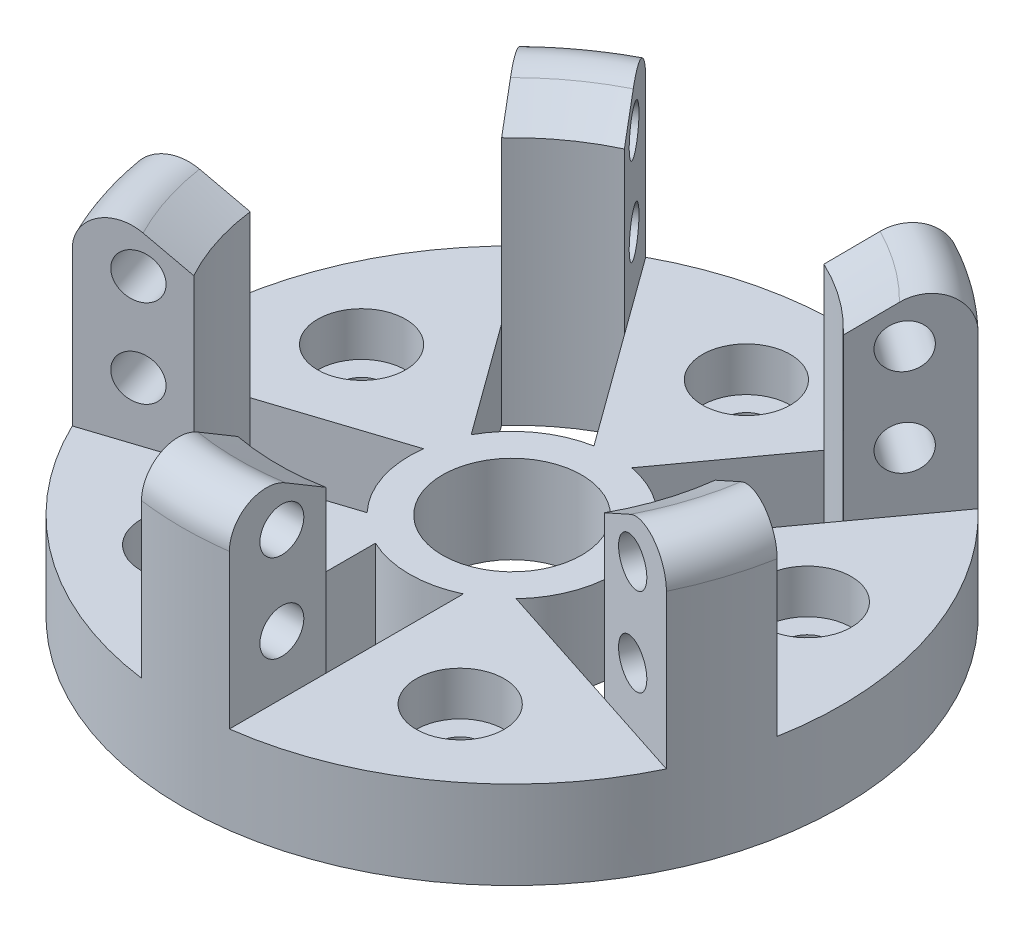
SolidWorks part; units mm, degrees
ref_plane "前视基准面" through (0, 0, 0) normal (0, 0, 1) x (1, 0, 0)
ref_plane "上视基准面" through (0, 0, 0) normal (0, 1, 0) x (1, 0, 0)
ref_plane "右视基准面" through (0, 0, 0) normal (1, 0, 0) x (0, 0, -1)
other "Configuration Table"
sketch "草图2" plane through (0, 0, 0) normal (1, 0, 0) x (0, 0, -1)
  line L0 (0, 43.5346) -> (0, -36.4026) construction
  line L1 (-63.5932, 0) -> (69.8336, 0) construction
  line L2 (0, 0) -> (-45, 0)
  line L3 (-45, 0) -> (-45, 33)
  line L4 (-37.4096, 37.2766) -> (-32, 34)
  line L5 (-32, 34) -> (-32, 12)
  line L6 (-32, 12) -> (0, 12)
  line L7 (0, 12) -> (0, 0)
  arc A0 (-37.4096, 37.2766) -> (-45, 33) centre (-40, 33) ccw
  dimension "D1" = 5
  dimension "D2" = 90
  dimension "D3" = 32
  dimension "D4" = 12
  dimension "D5" = 22
  dimension "D6" = 21
revolve "旋转1" add sketch "草图2" angle 360 about L0
sketch "草图3" plane through (0, 12, 0) normal (0, 1, 0) x (1, 0, 0)
  line L0 (0, 0) -> (0, -45) construction
  line L1 (0, 0) -> (-42.7975, -13.9058) construction
  line L2 (0, 0) -> (-26.4503, 36.4058) construction
  line L3 (0, 0) -> (26.4503, 36.4058) construction
  line L4 (0, 0) -> (42.7975, -13.9058) construction
  line L6 (6, -12.6491) -> (6, -44.5982)
  line L7 (-6, -12.6491) -> (-6, -44.5982)
  line L8 (-13.8841, 1.7975) -> (-44.2695, -8.0753)
  line L9 (-10.1759, -9.6151) -> (-40.5613, -19.4879)
  line L10 (-2.5809, 13.7601) -> (-21.3601, 39.6074)
  line L11 (-12.2891, 6.7066) -> (-31.0683, 32.554)
  line L12 (12.2891, 6.7066) -> (31.0683, 32.554)
  line L13 (2.5809, 13.7601) -> (21.3601, 39.6074)
  line L14 (10.1759, -9.6151) -> (40.5613, -19.4879)
  line L15 (13.8841, 1.7975) -> (44.2695, -8.0753)
  circle A0 centre (0, 0) radius 45 construction
  arc A1 (-40.5613, -19.4879) -> (-6, -44.5982) centre (0, 0) ccw
  arc A2 (-12.2891, 6.7066) -> (-13.8841, 1.7975) centre (0, 0) ccw
  arc A3 (6, -44.5982) -> (40.5613, -19.4879) centre (0, 0) ccw
  arc A4 (44.2695, -8.0753) -> (31.0683, 32.554) centre (0, 0) ccw
  arc A5 (21.3601, 39.6074) -> (-21.3601, 39.6074) centre (0, 0) ccw
  arc A6 (-31.0683, 32.554) -> (-44.2695, -8.0753) centre (0, 0) ccw
  arc A7 (2.5809, 13.7601) -> (-2.5809, 13.7601) centre (0, 0) ccw
  arc A8 (13.8841, 1.7975) -> (12.2891, 6.7066) centre (0, 0) ccw
  arc A9 (6, -12.6491) -> (10.1759, -9.6151) centre (0, 0) ccw
  arc A10 (-10.1759, -9.6151) -> (-6, -12.6491) centre (0, 0) ccw
  point P10 (0, 0)
  point P36 (0, 0)
  dimension "D1" = 28
  dimension "D2" = 5
  dimension "D3" = 12
  dimension "D4" = 5
extrude "切除-拉伸2" cut sketch "草图3" along normal through all contours L7 A1 L9 A10
sketch "草图6" plane through (0, 12, 0) normal (0, 1, 0) x (1, 0, 0)
  line L0 (-30.4419, 0) -> (28.6056, 0) construction
  line L1 (0, 24.2934) -> (0, -23.1923) construction
  line L2 (-6, -31.4325) -> (-6, -12.6491)
  line L3 (6, -31.4325) -> (6, -12.6491)
  line L4 (-31.7482, -4.0068) -> (-13.8841, 1.7975)
  line L5 (-28.04, -15.4195) -> (-10.1759, -9.6151)
  line L6 (-13.6214, 28.9561) -> (-2.5809, 13.7601)
  line L7 (-23.3296, 21.9027) -> (-12.2891, 6.7066)
  line L8 (23.3296, 21.9027) -> (12.2891, 6.7066)
  line L9 (13.6214, 28.9561) -> (2.5809, 13.7601)
  line L10 (28.04, -15.4195) -> (10.1759, -9.6151)
  line L11 (31.7482, -4.0068) -> (13.8841, 1.7975)
  circle A0 centre (0, 32) radius 3
  circle A1 centre (0, 0) radius 32 construction
  circle A2 centre (0, 0) radius 9.5
  arc A3 (-6, -12.6491) -> (6, -12.6491) centre (0, 0) ccw
  arc A4 (10.1759, -9.6151) -> (13.8841, 1.7975) centre (0, 0) ccw
  arc A5 (12.2891, 6.7066) -> (2.5809, 13.7601) centre (0, 0) ccw
  arc A6 (-2.5809, 13.7601) -> (-12.2891, 6.7066) centre (0, 0) ccw
  arc A7 (-13.8841, 1.7975) -> (-10.1759, -9.6151) centre (0, 0) ccw
  circle A8 centre (30.4338, 9.8885) radius 3
  circle A9 centre (18.8091, -25.8885) radius 3
  circle A10 centre (-18.8091, -25.8885) radius 3
  circle A11 centre (-30.4338, 9.8885) radius 3
  point P34 (0, 0)
  point P42 (0, 0)
  arc M1 (-31.7482, -4.0068) -> (-28.04, -15.4195) centre (0, 0) ccw
  arc M5 (-6, -31.4325) -> (6, -31.4325) centre (0, 0) ccw
  arc M9 (28.04, -15.4195) -> (31.7482, -4.0068) centre (0, 0) ccw
  arc M13 (23.3296, 21.9027) -> (13.6214, 28.9561) centre (0, 0) ccw
  arc M17 (-13.6214, 28.9561) -> (-23.3296, 21.9027) centre (0, 0) ccw
  dimension "D1" = 6
  dimension "D2" = 64
  dimension "D3" = 19
  dimension "D4" = 28
  dimension "D5" = 5
extrude "切除-拉伸3" cut sketch "草图6" against normal through all contours A5 L8 L9 M13 | A4 L10 L11 M9 | A3 L2 L3 M5 | A7 L4 L5 M1 | A6 L6 L7 M17 | A11 | A2 | A0 | A9 | A10 | A8
sketch "草图7" plane through (0, 12, 0) normal (0, 1, 0) x (1, 0, 0)
  line L20 (13.8841, 1.7975) -> (31.7482, -4.0068)
  line L21 (31.7482, -4.0068) -> (44.2695, -8.0753)
  line L22 (31.0683, 32.554) -> (23.3296, 21.9027)
  line L23 (23.3296, 21.9027) -> (12.2891, 6.7066)
  line L24 (2.5809, 13.7601) -> (13.6214, 28.9561)
  line L25 (13.6214, 28.9561) -> (21.3601, 39.6074)
  line L26 (-21.3601, 39.6074) -> (-13.6214, 28.9561)
  line L27 (-13.6214, 28.9561) -> (-2.5809, 13.7601)
  line L28 (-12.2891, 6.7066) -> (-23.3296, 21.9027)
  line L29 (-23.3296, 21.9027) -> (-31.0683, 32.554)
  line L30 (-44.2695, -8.0753) -> (-31.7482, -4.0068)
  line L31 (-31.7482, -4.0068) -> (-13.8841, 1.7975)
  line L32 (-10.1759, -9.6151) -> (-28.04, -15.4195)
  line L33 (-28.04, -15.4195) -> (-40.5613, -19.4879)
  line L34 (-6, -44.5982) -> (-6, -31.4325)
  line L35 (-6, -31.4325) -> (-6, -12.6491)
  line L36 (6, -12.6491) -> (6, -31.4325)
  line L37 (6, -31.4325) -> (6, -44.5982)
  line L38 (40.5613, -19.4879) -> (28.04, -15.4195)
  line L39 (28.04, -15.4195) -> (10.1759, -9.6151)
  line L40 (13.8841, 1.7975) -> (31.7482, -4.0068)
  line L41 (31.7482, -4.0068) -> (44.2695, -8.0753)
  line L42 (31.0683, 32.554) -> (23.3296, 21.9027)
  line L43 (23.3296, 21.9027) -> (12.2891, 6.7066)
  line L44 (2.5809, 13.7601) -> (13.6214, 28.9561)
  line L45 (13.6214, 28.9561) -> (21.3601, 39.6074)
  line L46 (-21.3601, 39.6074) -> (-13.6214, 28.9561)
  line L47 (-13.6214, 28.9561) -> (-2.5809, 13.7601)
  line L48 (-12.2891, 6.7066) -> (-23.3296, 21.9027)
  line L49 (-23.3296, 21.9027) -> (-31.0683, 32.554)
  line L50 (-44.2695, -8.0753) -> (-31.7482, -4.0068)
  line L51 (-31.7482, -4.0068) -> (-13.8841, 1.7975)
  line L52 (-10.1759, -9.6151) -> (-28.04, -15.4195)
  line L53 (-28.04, -15.4195) -> (-40.5613, -19.4879)
  line L54 (-6, -44.5982) -> (-6, -31.4325)
  line L55 (-6, -31.4325) -> (-6, -12.6491)
  line L56 (6, -12.6491) -> (6, -31.4325)
  line L57 (6, -31.4325) -> (6, -44.5982)
  line L58 (40.5613, -19.4879) -> (28.04, -15.4195)
  line L59 (28.04, -15.4195) -> (10.1759, -9.6151)
  circle A0 centre (0, 32) radius 3 construction
  circle A1 centre (30.4338, 9.8885) radius 3 construction
  circle A2 centre (18.8091, -25.8885) radius 3 construction
  circle A3 centre (-18.8091, -25.8885) radius 3 construction
  circle A4 centre (-30.4338, 9.8885) radius 3 construction
  circle A5 centre (0, 32) radius 3
  circle A6 centre (30.4338, 9.8885) radius 3
  circle A7 centre (18.8091, -25.8885) radius 3
  circle A8 centre (-18.8091, -25.8885) radius 3
  circle A9 centre (-30.4338, 9.8885) radius 3
  arc A10 (10.1759, -9.6151) -> (13.8841, 1.7975) centre (0, 0) ccw
  arc A11 (44.2695, -8.0753) -> (31.0683, 32.554) centre (0, 0) ccw
  arc A12 (12.2891, 6.7066) -> (2.5809, 13.7601) centre (0, 0) ccw
  arc A13 (21.3601, 39.6074) -> (-21.3601, 39.6074) centre (0, 0) ccw
  arc A14 (-2.5809, 13.7601) -> (-12.2891, 6.7066) centre (0, 0) ccw
  arc A15 (-31.0683, 32.554) -> (-44.2695, -8.0753) centre (0, 0) ccw
  arc A16 (-13.8841, 1.7975) -> (-10.1759, -9.6151) centre (0, 0) ccw
  arc A17 (-40.5613, -19.4879) -> (-6, -44.5982) centre (0, 0) ccw
  arc A18 (-6, -12.6491) -> (6, -12.6491) centre (0, 0) ccw
  arc A19 (6, -44.5982) -> (40.5613, -19.4879) centre (0, 0) ccw
  arc A20 (10.1759, -9.6151) -> (13.8841, 1.7975) centre (0, 0) ccw
  arc A21 (44.2695, -8.0753) -> (31.0683, 32.554) centre (0, 0) ccw
  arc A22 (12.2891, 6.7066) -> (2.5809, 13.7601) centre (0, 0) ccw
  arc A23 (21.3601, 39.6074) -> (-21.3601, 39.6074) centre (0, 0) ccw
  arc A24 (-2.5809, 13.7601) -> (-12.2891, 6.7066) centre (0, 0) ccw
  arc A25 (-31.0683, 32.554) -> (-44.2695, -8.0753) centre (0, 0) ccw
  arc A26 (-13.8841, 1.7975) -> (-10.1759, -9.6151) centre (0, 0) ccw
  arc A27 (-40.5613, -19.4879) -> (-6, -44.5982) centre (0, 0) ccw
  arc A28 (-6, -12.6491) -> (6, -12.6491) centre (0, 0) ccw
  arc A29 (6, -44.5982) -> (40.5613, -19.4879) centre (0, 0) ccw
  circle A30 centre (0, 32) radius 6
  circle A31 centre (30.4338, 9.8885) radius 6
  circle A32 centre (18.8091, -25.8885) radius 6
  circle A33 centre (-18.8091, -25.8885) radius 6
  circle A34 centre (-30.4338, 9.8885) radius 6
  circle A35 centre (0, 0) radius 22.3882
  point P64 (0, 0)
  circle M31 centre (-30.4338, 9.8885) radius 3
  circle M33 centre (0, 32) radius 3
  circle M34 centre (18.8091, -25.8885) radius 3
  circle M35 centre (-18.8091, -25.8885) radius 3
  circle M36 centre (30.4338, 9.8885) radius 3
  dimension "D2" = 12
  dimension "D3" = 44.7764
  dimension "D1" = 0
  dimension "D4" = 5
extrude "切除-拉伸4" cut sketch "草图7" against normal blind 6 contours A30 M33 | A34 M31 | A31 M36 | A32 M34 | A33 M35
sketch "草图8" plane through (-4.8541, 0, 3.5267) normal (-0.809, 0, 0.5878) x (0.5878, 0, 0.809)
  line L0 (-45, 0) -> (45, 0) construction
  line L1 (-45, 0) -> (45, 0)
  line L2 (-31.4325, 12) -> (-31.4325, 34) construction
  line L3 (-31.4325, 12) -> (-31.4325, 34)
  circle A0 centre (-37.4325, 32) radius 3
  circle A1 centre (-37.4325, 20) radius 3
  dimension "D1" = 6
  dimension "D2" = 20
  dimension "D3" = 6
  dimension "D4" = 12
extrude "切除-拉伸5" cut sketch "草图8" against normal up to next contours A0 | A1
pattern_circular "阵列(圆周)1" count 5 over 360 about axis through (0, 12, 0) along (0, 1, 0) of "切除-拉伸5"
